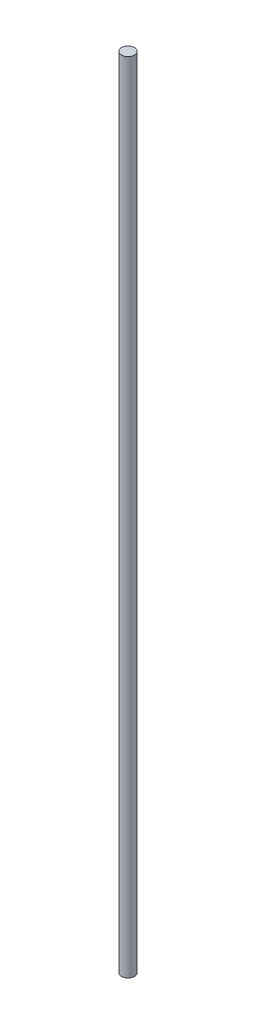
SolidWorks part; units mm, degrees
ref_plane "Front Plane" through (0, 0, 0) normal (0, 0, 1) x (1, 0, 0)
ref_plane "Top Plane" through (0, 0, 0) normal (0, 1, 0) x (1, 0, 0)
ref_plane "Right Plane" through (0, 0, 0) normal (1, 0, 0) x (0, 0, -1)
sketch "Sketch1" plane through (0, 0, 0) normal (0, 1, 0) x (1, 0, 0)
  circle A0 centre (0, 0) radius 4
  dimension "D1" = 8
extrude "Boss-Extrude1" add sketch "Sketch1" along normal blind 489.05
equation "\"d\"= 8"
equation "\"l\"= 489.05"
equation "\"D1@Boss-Extrude1\"=\"l\""
equation "\"D1@Sketch1\"=\"d\""
